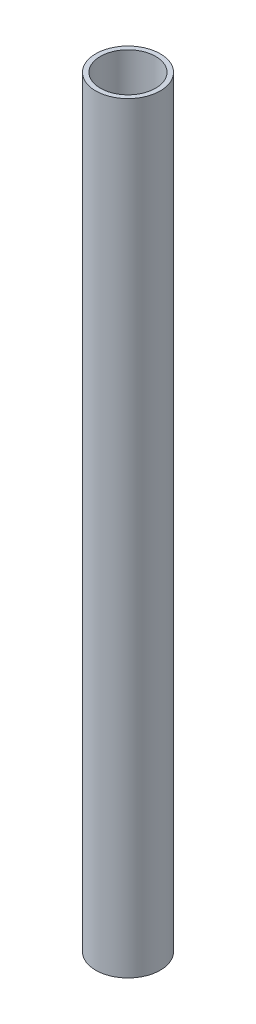
SolidWorks part; units mm, degrees
ref_plane "Front Plane" through (0, 0, 0) normal (0, 0, 1) x (1, 0, 0)
ref_plane "Top Plane" through (0, 0, 0) normal (0, 1, 0) x (1, 0, 0)
ref_plane "Right Plane" through (0, 0, 0) normal (1, 0, 0) x (0, 0, -1)
sketch "Sketch1" plane through (0, 0, 0) normal (0, 1, 0) x (1, 0, 0)
  circle A0 centre (0, 0) radius 38.1
  circle A1 centre (0, 0) radius 44.45
  dimension "D1" = 76.2
  dimension "D2" = 88.9
extrude "Boss-Extrude1" add sketch "Sketch1" along normal mid plane 1050.29
